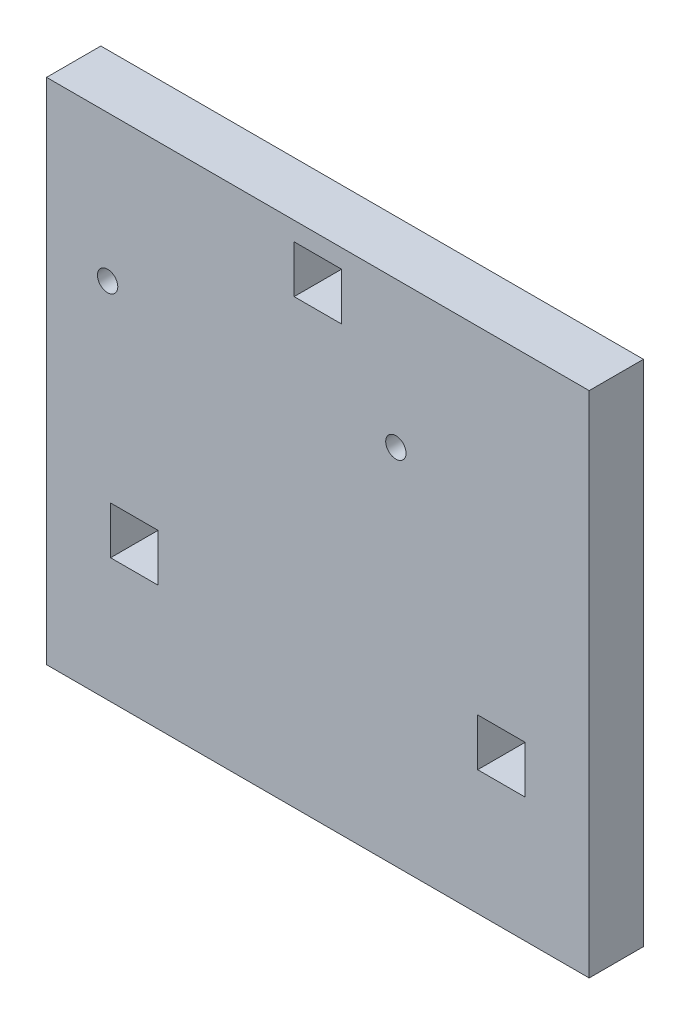
SolidWorks part; units mm, degrees
ref_plane "Front Plane" through (0, 0, 0) normal (0, 0, 1) x (1, 0, 0)
ref_plane "Top Plane" through (0, 0, 0) normal (0, 1, 0) x (1, 0, 0)
ref_plane "Right Plane" through (0, 0, 0) normal (1, 0, 0) x (0, 0, -1)
sketch "Sketch1" plane through (0, 0, 0) normal (0, 0, 1) x (1, 0, 0)
  line L1 (0, 0) -> (-160, 0)
  line L2 (0, 0) -> (0, -150)
  line L3 (0, -150) -> (-160, -150)
  line L4 (-160, 0) -> (-160, -150)
  dimension "D1" = 160
  dimension "D2" = 150
extrude "Boss-Extrude1" add sketch "Sketch1" along normal blind 16
sketch "Sketch2" plane through (0, 0, 16) normal (0, 0, 1) x (1, 0, 0)
  line L0 (-80, 0) -> (-80, -150) construction
  line L1 (0, 0) -> (-160, 0) construction
  line L2 (-160, -150) -> (0, -150) construction
  line L3 (-160, -75) -> (0, -75) construction
  line L4 (-80, -12.5) -> (-134.1266, -106.25) construction
  line L5 (0, -150) -> (0, 0) construction
  line L6 (-160, 0) -> (-160, -150) construction
  line L7 (-80, -12.5) -> (-25.8734, -106.25) construction
  line L8 (-134.1266, -106.25) -> (-25.8734, -106.25) construction
  line L10 (-73, -5.5) -> (-87, -5.5)
  line L11 (-73, -5.5) -> (-73, -19.5)
  line L12 (-73, -19.5) -> (-87, -19.5)
  line L13 (-87, -5.5) -> (-87, -19.5)
  line L14 (-73, -5.5) -> (-87, -19.5) construction
  line L15 (-73, -19.5) -> (-87, -5.5) construction
  line L16 (-127.1266, -113.25) -> (-141.1266, -113.25)
  line L17 (-127.1266, -113.25) -> (-127.1266, -99.25)
  line L18 (-127.1266, -99.25) -> (-141.1266, -99.25)
  line L19 (-141.1266, -113.25) -> (-141.1266, -99.25)
  line L20 (-127.1266, -113.25) -> (-141.1266, -99.25) construction
  line L21 (-127.1266, -99.25) -> (-141.1266, -113.25) construction
  line L22 (-18.8734, -113.25) -> (-32.8734, -113.25)
  line L23 (-18.8734, -113.25) -> (-18.8734, -99.25)
  line L24 (-18.8734, -99.25) -> (-32.8734, -99.25)
  line L25 (-32.8734, -113.25) -> (-32.8734, -99.25)
  line L26 (-18.8734, -113.25) -> (-32.8734, -99.25) construction
  line L27 (-18.8734, -99.25) -> (-32.8734, -113.25) construction
  circle A0 centre (-134.1266, -106.25) radius 7.5 construction
  circle A1 centre (-80, -12.5) radius 7.5 construction
  circle A2 centre (-25.8734, -106.25) radius 7.5 construction
  circle A4 centre (-80, -75) radius 62.5 construction
  dimension "D1" = 15
  dimension "D2" = 125
  dimension "D3" = 14
  dimension "D4" = 14
  dimension "D5" = 14
  dimension "D6" = 14
  dimension "D7" = 14
  dimension "D8" = 14
extrude "Cut-Extrude1" cut sketch "Sketch2" against normal blind 14
sketch "Sketch3" plane through (0, 0, 16) normal (0, 0, 1) x (1, 0, 0)
  line L1 (0, 0) -> (-160, 0) construction
  line L2 (-160, 0) -> (-160, -150) construction
  circle A0 centre (-57, -43) radius 3
  circle A1 centre (-142, -43) radius 3
  dimension "D1" = 6
  dimension "D2" = 6
  dimension "D3" = 18
  dimension "D4" = 103
  dimension "D6" = 43
  dimension "D5" = 43
extrude "Cut-Extrude2" cut sketch "Sketch3" against normal through all
